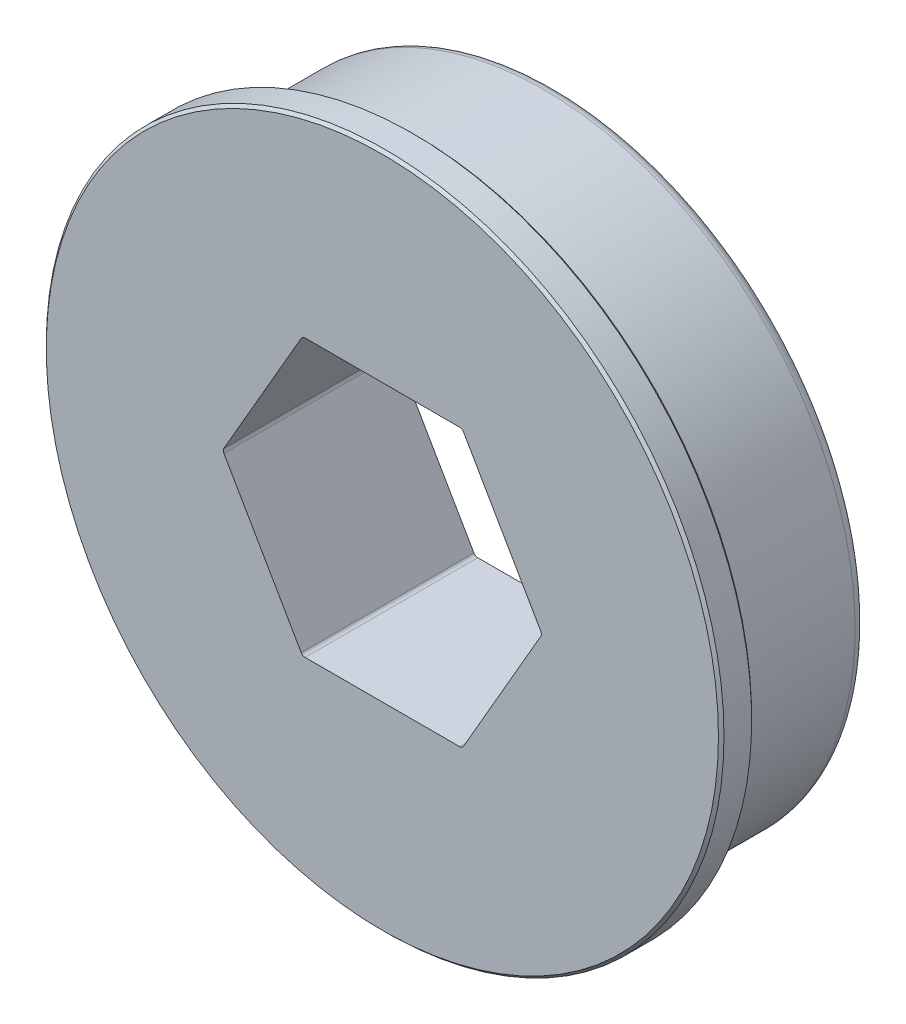
SolidWorks part; units mm, degrees
ref_plane "Front Plane" through (0, 0, 0) normal (0, 0, 1) x (1, 0, 0)
ref_plane "Top Plane" through (0, 0, 0) normal (0, 1, 0) x (1, 0, 0)
ref_plane "Right Plane" through (0, 0, 0) normal (1, 0, 0) x (0, 0, -1)
ref_plane "Plane1" through (0, 0, 0) normal (0, -1, 0) x (1, 0, 0)
sketch "Sketch1" plane through (0, 0, 0) normal (0, -1, 0) x (1, 0, 0)
  line L0 (15.5575, 7.9273) -> (0, 7.9273)
  line L1 (0, 7.9273) -> (0, 0)
  line L2 (0, 0) -> (14.2875, 0)
  line L3 (14.2875, 0) -> (14.2875, 5.8953)
  line L4 (14.2875, 5.8953) -> (13.97, 5.8953)
  line L5 (13.97, 5.8953) -> (13.97, 6.4033)
  line L6 (13.97, 6.4033) -> (15.5575, 6.4033)
  line L7 (15.5575, 6.4033) -> (15.5575, 7.9273)
  line L8 (0, 7.9273) -> (0, 0) construction
revolve "Revolve1" add sketch "Sketch1" angle 360 about L8
sketch "Sketch2" plane through (0, 0, 7.9273) normal (0, 0, 1) x (1, 0, 0)
  line L0 (-3.6662, -6.35) -> (3.6662, -6.35)
  line L1 (3.6662, -6.35) -> (7.3323, 0)
  line L2 (7.3323, 0) -> (3.6662, 6.35)
  line L3 (3.6662, 6.35) -> (-3.6662, 6.35)
  line L4 (-3.6662, 6.35) -> (-7.3323, 0)
  line L5 (-7.3323, 0) -> (-3.6662, -6.35)
extrude "Cut-Extrude1" cut sketch "Sketch2" against normal through all
chamfer "Chamfer1" distance 0.127 angle 45 2 edges at (-15.5575, 0, 6.4033) (-15.5575, 0, 7.9273)
fillet "Fillet1" radius 0.2032 6 edges at (3.6662, -6.35, 3.9637) (3.6662, 6.35, 3.9637) (-3.6662, 6.35, 3.9637) (7.3323, 0, 3.9637) (-7.3323, 0, 3.9637) (-3.6662, -6.35, 3.9637)
fillet "Fillet2" radius 0.508 1 edges at (-14.2875, 0, 0)
